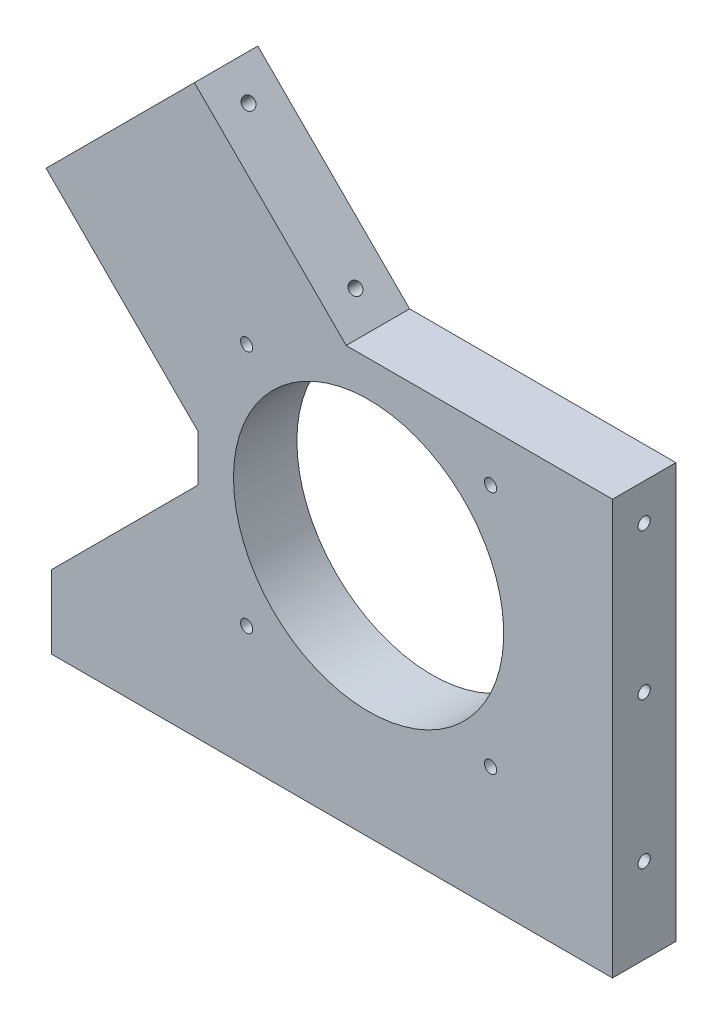
SolidWorks part; units mm, degrees
ref_plane "Front Plane" through (0, 0, 0) normal (0, 0, 1) x (1, 0, 0)
ref_plane "Top Plane" through (0, 0, 0) normal (0, 1, 0) x (1, 0, 0)
ref_plane "Right Plane" through (0, 0, 0) normal (1, 0, 0) x (0, 0, -1)
sketch "Sketch1" plane through (0, 0, 0) normal (0, 0, 1) x (1, 0, 0)
  line L0 (-50.9117, 50.9117) -> (0, 0) construction
  line L1 (50, 35) -> (50, -50)
  line L2 (50, -50) -> (-65, -50)
  line L4 (-50.9117, 50.9117) -> (-35.7089, 66.1145)
  line L5 (-50.9117, 50.9117) -> (-66.1145, 35.7089)
  line L7 (-4.5944, 35) -> (50, 35)
  line L10 (-65, -35) -> (-65, -50)
  line L11 (-25, 25) -> (25, 25) construction
  line L12 (25, 25) -> (25, -25) construction
  line L13 (25, -25) -> (-25, -25) construction
  line L14 (-25, -25) -> (-25, 25) construction
  line L17 (-35, -5) -> (-35, 4.5944)
  line L19 (-35.7089, 66.1145) -> (-4.5944, 35)
  line L20 (-66.1145, 35.7089) -> (-35, 4.5944)
  line L21 (-65, -35) -> (-35, -5)
  circle A0 centre (0, 0) radius 27.7
  circle A1 centre (-25, 25) radius 1.25
  circle A2 centre (25, 25) radius 1.25
  circle A3 centre (25, -25) radius 1.25
  circle A4 centre (-25, -25) radius 1.25
  dimension "D3" = 55.4
  dimension "D16" = 2.5
  dimension "D17" = 2.5
  dimension "D18" = 2.5
  dimension "D19" = 2.5
  dimension "D2" = 50
  dimension "D4" = 50
  dimension "D5" = 72
  dimension "D6" = 21.5
  dimension "D7" = 21.5
  dimension "D8" = 85
  dimension "D9" = 135
  dimension "D10" = 65
  dimension "D11" = 44.0025
  dimension "D12" = 35
  dimension "D13" = 50
  dimension "D14" = 25
  dimension "D15" = 25
  dimension "D20" = 135
extrude "Boss-Extrude1" add sketch "Sketch1" along normal blind 13
sketch "Sketch2" plane through (-15.2028, -15.2028, 0) normal (-0.7071, -0.7071, 0) x (0, 0, 1)
  line L0 (13, 72) -> (13, 27.9975) construction
  line L1 (13, 72) -> (0, 72) construction
  circle A0 centre (6.5, 65.5) radius 1.25
  circle A1 centre (6.5, 34.5) radius 1.25
  dimension "D1" = 2.5
  dimension "D2" = 2.5
  dimension "D3" = 6.5
  dimension "D4" = 6.5
  dimension "D5" = 6.5
  dimension "D6" = 31
extrude "Cut-Extrude1" cut sketch "Sketch2" against normal up to next
sketch "Sketch3" plane through (0, -50, 0) normal (0, -1, 0) x (1, 0, 0)
  line L0 (-65, 0) -> (50, 0) construction
  line L1 (50, 13) -> (50, 0) construction
  line L2 (-65, 13) -> (-65, 0) construction
  circle A0 centre (-57.5, 6.5) radius 1.25
  circle A1 centre (32.5, 6.5) radius 1.25
  circle A2 centre (-12.5, 6.5) radius 1.25
  point P12 (0, 0)
  dimension "D1" = 2.5
  dimension "D2" = 2.5
  dimension "D7" = 2.5
  dimension "D3" = 6.5
  dimension "D4" = 6.5
  dimension "D5" = 17.5
  dimension "D6" = 7.5
  dimension "D8" = 45
extrude "Cut-Extrude2" cut sketch "Sketch3" against normal blind 15
sketch "Sketch4" plane through (50, 0, 0) normal (1, 0, 0) x (0, 0, -1)
  line L0 (-13, -50) -> (0, -50) construction
  line L1 (-13, -50) -> (-13, 35) construction
  line L2 (-13, 35) -> (0, 35) construction
  line L3 (0, -50) -> (0, 35) construction
  circle A0 centre (-6.5, -32.5) radius 1.25
  circle A1 centre (-6.5, 27.5) radius 1.25
  circle A2 centre (-6.5, -2.5) radius 1.25
  dimension "D3" = 2.5
  dimension "D5" = 2.5
  dimension "D7" = 2.5
  dimension "D1" = 17.5
  dimension "D2" = 6.5
  dimension "D4" = 7.5
  dimension "D6" = 6.5
  dimension "D8" = 30
  dimension "D9" = 6.5
extrude "Cut-Extrude3" cut sketch "Sketch4" against normal blind 15
